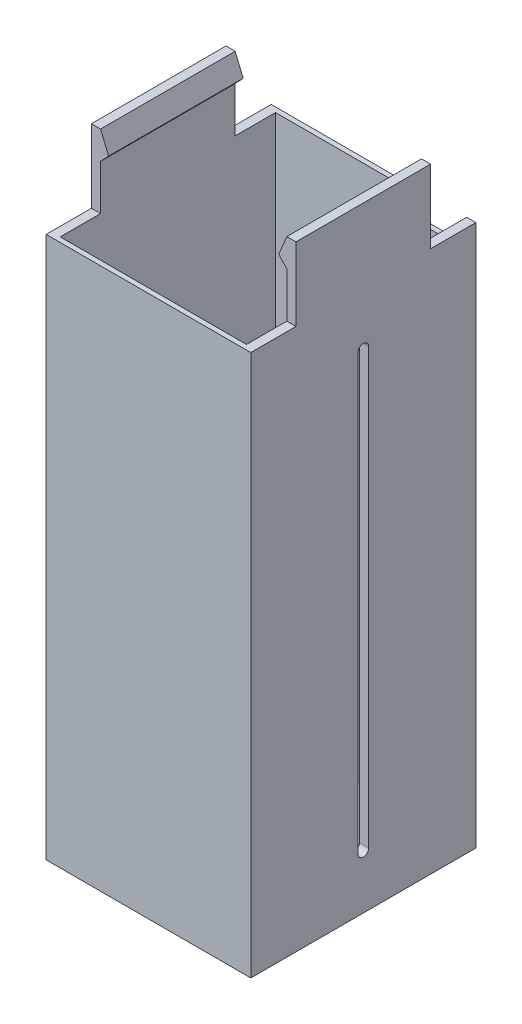
SolidWorks part; units mm, degrees
ref_plane "Front Plane" through (0, 0, 0) normal (0, 0, 1) x (1, 0, 0)
ref_plane "Top Plane" through (0, 0, 0) normal (0, 1, 0) x (1, 0, 0)
ref_plane "Right Plane" through (0, 0, 0) normal (1, 0, 0) x (0, 0, -1)
sketch "Sketch1" plane through (0, 0, 0) normal (0, 1, 0) x (1, 0, 0)
  line L0 (-19, 20.9) -> (42.3707, 20.9) construction
  line L1 (-19, 20.9) -> (19, 20.9)
  line L2 (-19, 20.9) -> (-19, -20.9)
  line L3 (-19, -20.9) -> (19, -20.9)
  line L4 (19, 20.9) -> (19, -20.9)
  line L5 (-19, 20.9) -> (19, -20.9) construction
  line L6 (-19, -20.9) -> (19, 20.9) construction
  line L7 (17.3, 20) -> (-17.3, 20)
  line L8 (17.3, 20) -> (17.3, -20)
  line L9 (17.3, -20) -> (-17.3, -20)
  line L10 (-17.3, 20) -> (-17.3, -20)
  line L11 (17.3, 20) -> (-17.3, -20) construction
  line L12 (17.3, -20) -> (-17.3, 20) construction
  point P0 (0, 0)
  point P6 (0, 0)
  dimension "D1" = 34.6
  dimension "D2" = 40
  dimension "D3" = 1.7
  dimension "D5" = 0.9
extrude "Boss-Extrude1" add sketch "Sketch1" along normal blind 100
sketch "Sketch2" plane through (0, 100, 0) normal (0, 1, 0) x (1, 0, 0)
  line L0 (-23.425, 0) -> (23.575, 0) construction
  line L1 (-19, 20.9) -> (-19, -20.9) construction
  line L3 (-17.3, 24.7662) -> (-17.3, -22.0296) construction
  line L4 (0, 23.9453) -> (0, -27.2839) construction
  line L5 (17.3, 12.5) -> (19, 12.5)
  line L6 (-17.3, -12.5) -> (-19, -12.5)
  line L7 (-17.3, -12.5) -> (-17.3, 12.5)
  line L8 (-17.3, 12.5) -> (-19, 12.5)
  line L9 (-19, -12.5) -> (-19, 12.5)
  line L10 (-17.3, -12.5) -> (-19, 12.5) construction
  line L11 (-17.3, 12.5) -> (-19, -12.5) construction
  line L12 (19, -12.5) -> (19, 12.5)
  line L13 (17.3, -12.5) -> (19, -12.5)
  line L14 (17.3, -12.5) -> (17.3, 12.5)
  line L15 (-17.3, 20) -> (-17.3, -20) construction
  point P11 (-18.15, 0)
  dimension "D2" = 25
  dimension "D3" = 20
extrude "Boss-Extrude2" add sketch "Sketch2" along normal blind 13.6
sketch "Sketch5" plane through (0, 0, 12.5) normal (0, 0, 1) x (1, 0, 0)
  line L0 (-15.8, 110) -> (15.8, 110) construction
  line L1 (17.3, 113.6) -> (17.3, 100) construction
  line L4 (-15.8, 110) -> (-17.3, 108.4)
  line L5 (-17.3, 108.4) -> (-17.3, 113.6)
  line L7 (-17.3, 113.6) -> (-15.8, 110)
  line L8 (17.3, 108.4) -> (17.3, 113.6)
  line L9 (15.8, 110) -> (17.3, 108.4)
  line L10 (17.3, 113.6) -> (15.8, 110)
  line L11 (-17.3, 113.6) -> (-17.3, 100) construction
  dimension "D1" = 10
  dimension "D2" = 1.6
  dimension "D3" = 1.5
  dimension "D4" = 1.6
  dimension "D5" = 1.5
extrude "Boss-Extrude5" add sketch "Sketch5" against normal up to surface (25 mm away) up to face at (18.15, 106.8, -12.5)
sketch "Sketch6" plane through (0, 0, 0) normal (0, -1, 0) x (1, 0, 0)
  line L0 (-19, 20.9) -> (19, 20.9) construction
  line L1 (19, 20.9) -> (-19, 20.9)
  line L2 (19, 20.9) -> (19, -20.9)
  line L3 (19, -20.9) -> (-19, -20.9)
  line L4 (-19, 20.9) -> (-19, -20.9)
extrude "Boss-Extrude6" add sketch "Sketch6" along normal blind 0.6
sketch "Sketch7" plane through (0, 0, -20.9) normal (0, 0, -1) x (-1, 0, 0)
  line L1 (-17.3, 100) -> (-4, 100)
  line L2 (-17.3, 100) -> (-17.3, 95.6)
  line L3 (-17.3, 95.6) -> (-4, 95.6)
  line L4 (-4, 100) -> (-4, 95.6)
  line L5 (-19, 100) -> (19, 100) construction
  line L6 (-19, 100) -> (-19, -0.6) construction
  dimension "D1" = 1.7
  dimension "D2" = 4.4
  dimension "D3" = 13.3
extrude "Cut-Extrude1" cut sketch "Sketch7" against normal blind 10
sketch "Sketch8" plane through (19, 0, 0) normal (1, 0, 0) x (0, 0, -1)
  line L0 (0, -0.6) -> (0, 113.6) construction
  line L1 (20.9, -0.6) -> (-20.9, -0.6) construction
  line L2 (-12.5, 113.6) -> (12.5, 113.6) construction
  line L3 (0, 9.4) -> (0, 90) construction
  line L4 (-1, 9.4) -> (-1, 90)
  line L5 (1, 9.4) -> (1, 90)
  line L6 (12.5, 100) -> (20.9, 100) construction
  arc A0 (-1, 9.4) -> (1, 9.4) centre (0, 9.4) ccw
  arc A1 (1, 90) -> (-1, 90) centre (0, 90) ccw
  point P8 (0, 49.7)
  dimension "D1" = 2
  dimension "D2" = 10
  dimension "D3" = 10
extrude "Cut-Extrude2" cut sketch "Sketch8" against normal blind 10
